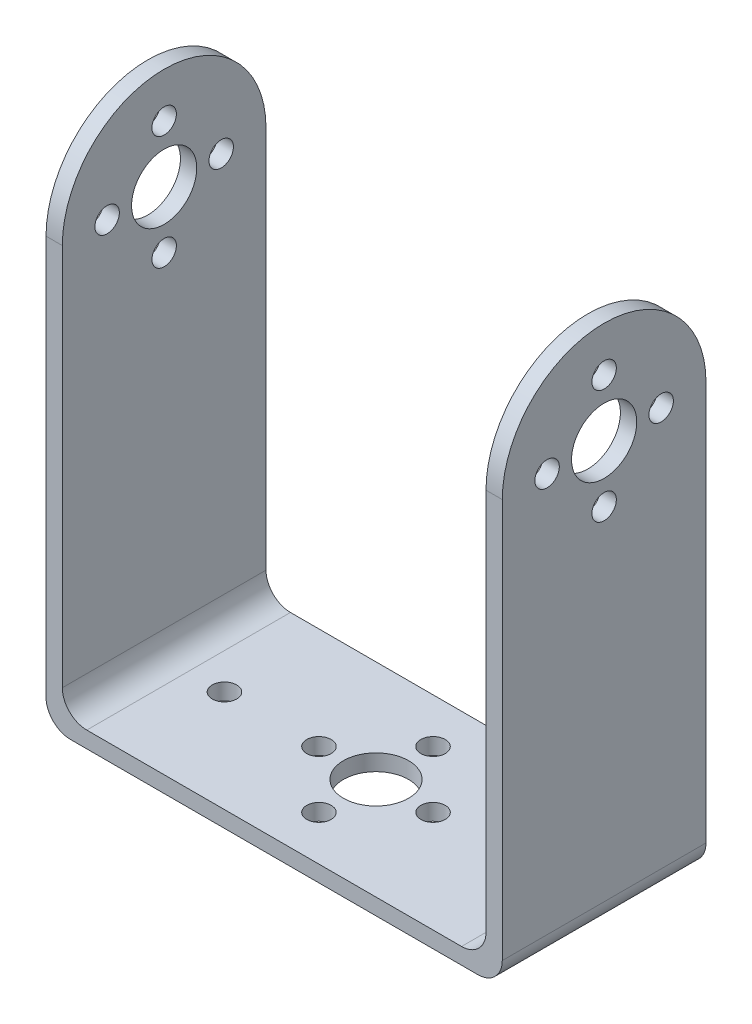
SolidWorks part; units mm, degrees
ref_plane "前视基准面" through (0, 0, 0) normal (0, 0, 1) x (1, 0, 0)
ref_plane "上视基准面" through (0, 0, 0) normal (0, 1, 0) x (1, 0, 0)
ref_plane "右视基准面" through (0, 0, 0) normal (1, 0, 0) x (0, 0, -1)
sketch "草图1" plane through (0, 0, 0) normal (0, 1, 0) x (1, 0, 0)
  line L0 (26, -25) -> (26, 0) construction
  line L1 (0, 0) -> (52, 0)
  line L2 (0, 0) -> (0, -25)
  line L3 (0, -25) -> (52, -25)
  line L4 (52, 0) -> (52, -25)
  line L5 (0, -12.5) -> (52, -12.5) construction
  circle A0 centre (44.6, -12.5) radius 1.5
  circle A1 centre (26, -12.5) radius 4
  circle A2 centre (26, -19.5) radius 1.5
  circle A3 centre (19, -12.5) radius 1.5
  circle A4 centre (26, -5.5) radius 1.5
  circle A5 centre (33, -12.5) radius 1.5
  circle A6 centre (7.4, -12.5) radius 1.5
  point P24 (26, -12.5)
  dimension "D3" = 3
  dimension "D5" = 8
  dimension "D6" = 3
  dimension "D7" = 7
  dimension "D1" = 52
  dimension "D2" = 25
  dimension "D4" = 18.6
  dimension "D8" = 4
extrude "凸台-拉伸1" add sketch "草图1" along normal blind 2
sketch "草图2" plane through (0, 0, 0) normal (0, 1, 0) x (1, 0, 0)
  line L0 (52, 0) -> (0, 0) construction
  line L1 (0, -25) -> (-2, -25)
  line L2 (0, -25) -> (0, 0)
  line L3 (0, 0) -> (-2, 0)
  line L4 (-2, -25) -> (-2, 0)
  line L6 (52, -25) -> (54, -25)
  line L7 (52, -25) -> (52, 0)
  line L8 (52, 0) -> (54, 0)
  line L9 (54, -25) -> (54, 0)
  dimension "D1" = 2
  dimension "D2" = 2
extrude "凸台-拉伸2" add sketch "草图2" along normal blind 64.5
sketch "草图3" plane through (-2, 0, 0) normal (-1, 0, 0) x (0, 0, 1)
  line L0 (0, 64.5) -> (0, 0) construction
  line L1 (25, 64.5) -> (25, 0) construction
  line L2 (0, 64.5) -> (25, 64.5) construction
  line L3 (0, 52) -> (0, 64.5)
  line L4 (0, 64.5) -> (25, 64.5)
  line L5 (25, 64.5) -> (25, 52)
  line L6 (0, 52) -> (25, 52) construction
  arc A0 (0, 52) -> (25, 52) centre (12.5, 52) cw
  circle A1 centre (12.5, 52) radius 4
  circle A2 centre (12.5, 59) radius 1.5
  circle A3 centre (19.5, 52) radius 1.5
  circle A4 centre (12.5, 45) radius 1.5
  circle A5 centre (5.5, 52) radius 1.5
  point P25 (12.5, 52)
  line M5 (25, 0) -> (25, 64.5)
  line M6 (25, 64.5) -> (0, 64.5)
  line M7 (0, 64.5) -> (0, 0)
  dimension "D1" = 8
  dimension "D2" = 3
  dimension "D3" = 7
  dimension "D4" = 4
extrude "切除-拉伸2" cut sketch "草图3" against normal up to surface (56 mm away) contours A0 L4 M7 | A0 M6 M5 | L6 A1 | A1 L6 | A4 | A2 | A5 | A3 up to face at (54, 32.25, 12.5)
fillet "圆角1" radius 3 4 edges at (0, 2, 12.5) (54, 0, 12.5) (52, 2, 12.5) (-2, 0, 12.5)
